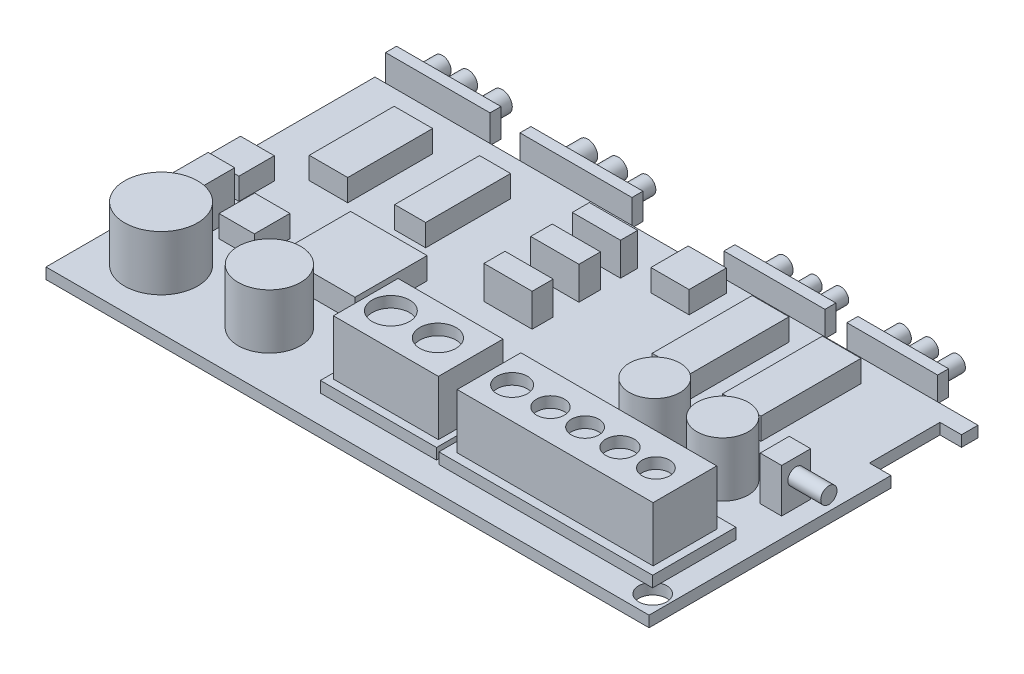
SolidWorks part; units mm, degrees
ref_plane "Front Plane" through (0, 0, 0) normal (0, 0, 1) x (1, 0, 0)
ref_plane "Top Plane" through (0, 0, 0) normal (0, 1, 0) x (1, 0, 0)
ref_plane "Right Plane" through (0, 0, 0) normal (1, 0, 0) x (0, 0, -1)
sketch "Sketch1" plane through (0, 0, 0) normal (0, 1, 0) x (1, 0, 0)
  line L1 (-48.7641, 18.8973) -> (6.2359, 18.8973)
  line L2 (-48.7641, 18.8973) -> (-48.7641, -11.1027)
  line L3 (-48.7641, -11.1027) -> (6.2359, -11.1027)
  line L4 (6.2359, 18.8973) -> (6.2359, -11.1027)
  line L5 (-48.7641, 18.8973) -> (6.2359, -11.1027) construction
  line L6 (-48.7641, -11.1027) -> (6.2359, 18.8973) construction
  point P0 (-21.2641, 3.8973)
  dimension "D1" = 30
  dimension "D2" = 55
extrude "Boss-Extrude1" add sketch "Sketch1" along normal blind 1
sketch "Sketch2" plane through (0, 1, 0) normal (0, 1, 0) x (1, 0, 0)
  line L1 (-15.244, -1.1981) -> (4.2477, -1.1981)
  line L2 (-15.244, -1.1981) -> (-15.244, -8.7905)
  line L3 (-15.244, -8.7905) -> (4.2477, -8.7905)
  line L4 (4.2477, -1.1981) -> (4.2477, -8.7905)
  line L5 (-15.244, -1.1981) -> (4.2477, -8.7905) construction
  line L6 (-15.244, -8.7905) -> (4.2477, -1.1981) construction
  point P0 (-5.4982, -4.9943)
extrude "Boss-Extrude2" add sketch "Sketch2" along normal blind 1
sketch "Sketch3" plane through (0, 2, 0) normal (0, 1, 0) x (1, 0, 0)
  line L1 (-14.3341, -2.2268) -> (3.5346, -2.2268)
  line L2 (-14.3341, -2.2268) -> (-14.3341, -8.0333)
  line L3 (-14.3341, -8.0333) -> (3.5346, -8.0333)
  line L4 (3.5346, -2.2268) -> (3.5346, -8.0333)
extrude "Boss-Extrude3" add sketch "Sketch3" along normal blind 5
sketch "Sketch4" plane through (0, 7, 0) normal (0, 1, 0) x (1, 0, 0)
  circle A0 centre (-12.1871, -5.1676) radius 1.388
  circle A1 centre (-8.6894, -5.1676) radius 1.271
  circle A2 centre (-5.534, -5.1676) radius 1.2522
  circle A3 centre (-2.3491, -5.1676) radius 1.299
  circle A4 centre (0.924, -5.1676) radius 1.2507
extrude "Cut-Extrude1" cut sketch "Sketch4" against normal blind 1
sketch "Sketch5" plane through (0, 1, 0) normal (0, 1, 0) x (1, 0, 0)
  line L1 (-26.2894, -1.2801) -> (-15.6991, -1.2801)
  line L2 (-26.2894, -1.2801) -> (-26.2894, -8.5533)
  line L3 (-26.2894, -8.5533) -> (-15.6991, -8.5533)
  line L4 (-15.6991, -1.2801) -> (-15.6991, -8.5533)
extrude "Boss-Extrude4" add sketch "Sketch5" along normal blind 1
sketch "Sketch6" plane through (0, 2, 0) normal (0, 1, 0) x (1, 0, 0)
  line L1 (-25.8004, -1.9557) -> (-16.2286, -1.9557)
  line L2 (-25.8004, -1.9557) -> (-25.8004, -7.8518)
  line L3 (-25.8004, -7.8518) -> (-16.2286, -7.8518)
  line L4 (-16.2286, -1.9557) -> (-16.2286, -7.8518)
extrude "Boss-Extrude5" add sketch "Sketch6" along normal blind 5
sketch "Sketch7" plane through (0, 7, 0) normal (0, 1, 0) x (1, 0, 0)
  circle A0 centre (-23.5786, -4.8348) radius 1.7049
  circle A1 centre (-19.2874, -4.8348) radius 1.6528
extrude "Cut-Extrude2" cut sketch "Sketch7" against normal blind 1
sketch "Sketch8" plane through (0, 1, 0) normal (0, 1, 0) x (1, 0, 0)
  line L1 (-26.0722, 15.7653) -> (-21.6753, 15.7653)
  line L2 (-26.0722, 15.7653) -> (-26.0722, 14.2045)
  line L3 (-26.0722, 14.2045) -> (-21.6753, 14.2045)
  line L4 (-21.6753, 15.7653) -> (-21.6753, 14.2045)
  line L5 (-26.0722, 12.3762) -> (-21.6753, 12.3762)
  line L6 (-26.0722, 12.3762) -> (-26.0722, 10.4103)
  line L7 (-26.0722, 10.4103) -> (-21.6753, 10.4103)
  line L8 (-21.6753, 12.3762) -> (-21.6753, 10.4103)
  line L9 (-26.0722, 8.068) -> (-21.6753, 8.068)
  line L10 (-26.0722, 8.068) -> (-26.0722, 6.1445)
  line L11 (-26.0722, 6.1445) -> (-21.6753, 6.1445)
  line L12 (-21.6753, 8.068) -> (-21.6753, 6.1445)
extrude "Boss-Extrude6" add sketch "Sketch8" along normal blind 3
sketch "Sketch9" plane through (0, 1, 0) normal (0, 1, 0) x (1, 0, 0)
  line L1 (-43.5801, 15.466) -> (-40.0688, 15.466)
  line L2 (-43.5801, 15.466) -> (-43.5801, 7.7221)
  line L3 (-43.5801, 7.7221) -> (-40.0688, 7.7221)
  line L4 (-40.0688, 15.466) -> (-40.0688, 7.7221)
  line L5 (-35.7901, 15.466) -> (-32.9619, 15.466)
  line L6 (-35.7901, 15.466) -> (-35.7901, 7.7221)
  line L7 (-35.7901, 7.7221) -> (-32.9619, 7.7221)
  line L8 (-32.9619, 15.466) -> (-32.9619, 7.7221)
  line L9 (-12.3048, 16.8422) -> (-8.9472, 16.8422)
  line L10 (-12.3048, 16.8422) -> (-12.3048, 7.7221)
  line L11 (-12.3048, 7.7221) -> (-8.9472, 7.7221)
  line L12 (-8.9472, 16.8422) -> (-8.9472, 7.7221)
  line L13 (-5.8988, 16.8422) -> (-2.383, 16.8422)
  line L14 (-5.8988, 16.8422) -> (-5.8988, 7.7221)
  line L15 (-5.8988, 7.7221) -> (-2.383, 7.7221)
  line L16 (-2.383, 16.8422) -> (-2.383, 7.7221)
extrude "Boss-Extrude7" add sketch "Sketch9" along normal blind 2
sketch "Sketch11" plane through (0, 0, -18.8973) normal (0, 0, -1) x (-1, 0, 0)
  line L1 (47.7942, 0.8392) -> (38.2673, 0.8392)
  line L2 (47.7942, 0.8392) -> (47.7942, 3.4201)
  line L3 (47.7942, 3.4201) -> (38.2673, 3.4201)
  line L4 (38.2673, 0.8392) -> (38.2673, 3.4201)
extrude "Boss-Extrude9" add sketch "Sketch11" along normal blind 1
sketch "Sketch12" plane through (0, 0, -18.8973) normal (0, 0, -1) x (-1, 0, 0)
  line L1 (35.5379, 0.8065) -> (25.323, 0.8065)
  line L2 (35.5379, 0.8065) -> (35.5379, 3.2057)
  line L3 (35.5379, 3.2057) -> (25.323, 3.2057)
  line L4 (25.323, 0.8065) -> (25.323, 3.2057)
extrude "Boss-Extrude10" add sketch "Sketch12" along normal blind 1
sketch "Sketch13" plane through (0, 0, -18.8973) normal (0, 0, -1) x (-1, 0, 0)
  line L1 (16.9357, 0.8586) -> (7.7247, 0.8586)
  line L2 (16.9357, 0.8586) -> (16.9357, 3.1734)
  line L3 (16.9357, 3.1734) -> (7.7247, 3.1734)
  line L4 (7.7247, 0.8586) -> (7.7247, 3.1734)
extrude "Boss-Extrude11" add sketch "Sketch13" along normal blind 1
sketch "Sketch14" plane through (0, 0, -18.8973) normal (0, 0, -1) x (-1, 0, 0)
  line L1 (5.7159, 0.8682) -> (-2.5533, 0.8682)
  line L2 (5.7159, 0.8682) -> (5.7159, 3.1213)
  line L3 (5.7159, 3.1213) -> (-2.5533, 3.1213)
  line L4 (-2.5533, 0.8682) -> (-2.5533, 3.1213)
extrude "Boss-Extrude12" add sketch "Sketch14" along normal blind 1
sketch "Sketch15" plane through (0, 1, 0) normal (0, 1, 0) x (1, 0, 0)
  circle A0 centre (-7.2525, 2.9007) radius 2.3196
  circle A1 centre (-1.0581, 2.9007) radius 2.3354
  circle A2 centre (-33.782, -5.7107) radius 2.8507
  circle A3 centre (-43.6603, -5.7107) radius 3.3249
extrude "Boss-Extrude13" add sketch "Sketch15" along normal blind 5
sketch "Sketch16" plane through (0, 1, 0) normal (0, 1, 0) x (1, 0, 0)
  circle A0 centre (-51.5765, 22.0167) radius 1.1752
  circle A1 centre (-51.5765, -8.8482) radius 1.2523
  circle A2 centre (4.2363, 22.0167) radius 1.3215
  circle A3 centre (4.7164, -9.2489) radius 1.2762
extrude "Cut-Extrude3" cut sketch "Sketch16" against normal blind 5
sketch "Sketch17" plane through (0, 1, 0) normal (0, 1, 0) x (1, 0, 0)
  line L1 (-53.9715, 18.7195) -> (-50.3994, 18.7195)
  line L2 (-53.9715, 18.7195) -> (-53.9715, 12.9424)
  line L3 (-53.9715, 12.9424) -> (-50.3994, 12.9424)
  line L4 (-50.3994, 18.7195) -> (-50.3994, 12.9424)
  line L5 (7.3455, 17.3919) -> (4.2736, 17.3919)
  line L6 (7.3455, 17.3919) -> (7.3455, 10.9573)
  line L7 (7.3455, 10.9573) -> (4.2736, 10.9573)
  line L8 (4.2736, 17.3919) -> (4.2736, 10.9573)
extrude "Cut-Extrude4" cut sketch "Sketch17" against normal blind 5
sketch "Sketch18" plane through (0, 1, 0) normal (0, 1, 0) x (1, 0, 0)
  line L1 (-37.264, 5.1763) -> (-30.283, 5.1763)
  line L2 (-37.264, 5.1763) -> (-37.264, -1.4025)
  line L3 (-37.264, -1.4025) -> (-30.283, -1.4025)
  line L4 (-30.283, 5.1763) -> (-30.283, -1.4025)
  line L5 (-48.2249, 6.0943) -> (-45.1384, 6.0943)
  line L6 (-48.2249, 6.0943) -> (-48.2249, 2.8671)
  line L7 (-48.2249, 2.8671) -> (-45.1384, 2.8671)
  line L8 (-45.1384, 6.0943) -> (-45.1384, 2.8671)
  line L9 (-43.0944, 2.2514) -> (-39.8727, 2.2514)
  line L10 (-43.0944, 2.2514) -> (-43.0944, -0.9889)
  line L11 (-43.0944, -0.9889) -> (-39.8727, -0.9889)
  line L12 (-39.8727, 2.2514) -> (-39.8727, -0.9889)
  line L13 (-19.1381, 17.8423) -> (-15.6557, 17.8423)
  line L14 (-19.1381, 17.8423) -> (-19.1381, 14.4374)
  line L15 (-19.1381, 14.4374) -> (-15.6557, 14.4374)
  line L16 (-15.6557, 17.8423) -> (-15.6557, 14.4374)
extrude "Boss-Extrude14" add sketch "Sketch18" along normal blind 2
sketch "Sketch19" plane through (0, 0, -19.8973) normal (0, 0, -1) x (-1, 0, 0)
  circle A0 centre (-1.367, 1.9737) radius 0.7198
  circle A1 centre (1.1068, 1.9737) radius 0.7603
  circle A2 centre (3.6005, 1.7955) radius 0.7583
  circle A3 centre (9.2798, 1.9737) radius 0.7167
  circle A4 centre (11.6193, 1.7955) radius 0.6459
  circle A5 centre (14.4138, 1.7955) radius 0.7893
  circle A6 centre (26.9357, 1.8984) radius 0.7889
  circle A7 centre (29.586, 1.8984) radius 0.8785
  circle A8 centre (32.3531, 1.8984) radius 0.9083
  circle A9 centre (40.1596, 1.8984) radius 0.9202
  circle A10 centre (43.253, 1.9737) radius 0.8478
  circle A11 centre (45.6267, 1.9737) radius 0.8133
extrude "Boss-Extrude15" add sketch "Sketch19" along normal blind 2
sketch "Sketch20" plane through (0, 1, 0) normal (0, 1, 0) x (1, 0, 0)
  line L1 (-43.9992, 1.3434) -> (-46.4197, 1.3434)
  line L2 (-43.9992, 1.3434) -> (-43.9992, -2.1353)
  line L3 (-43.9992, -2.1353) -> (-46.4197, -2.1353)
  line L4 (-46.4197, 1.3434) -> (-46.4197, -2.1353)
extrude "Boss-Extrude17" add sketch "Sketch20" along normal blind 4
sketch "Sketch22" plane through (0, 1, 0) normal (0, 1, 0) x (1, 0, 0)
  line L1 (4.4593, 5.4147) -> (2.5027, 5.4147)
  line L2 (4.4593, 5.4147) -> (4.4593, 2.7669)
  line L3 (4.4593, 2.7669) -> (2.5027, 2.7669)
  line L4 (2.5027, 5.4147) -> (2.5027, 2.7669)
extrude "Boss-Extrude19" add sketch "Sketch22" along normal blind 4
sketch "Sketch23" plane through (4.4593, 0, 0) normal (1, 0, 0) x (0, 0, -1)
  circle A0 centre (4.0719, 3.5017) radius 0.7405
  point P2 (4.0719, 3.5017)
extrude "Boss-Extrude20" add sketch "Sketch23" along normal blind 3
